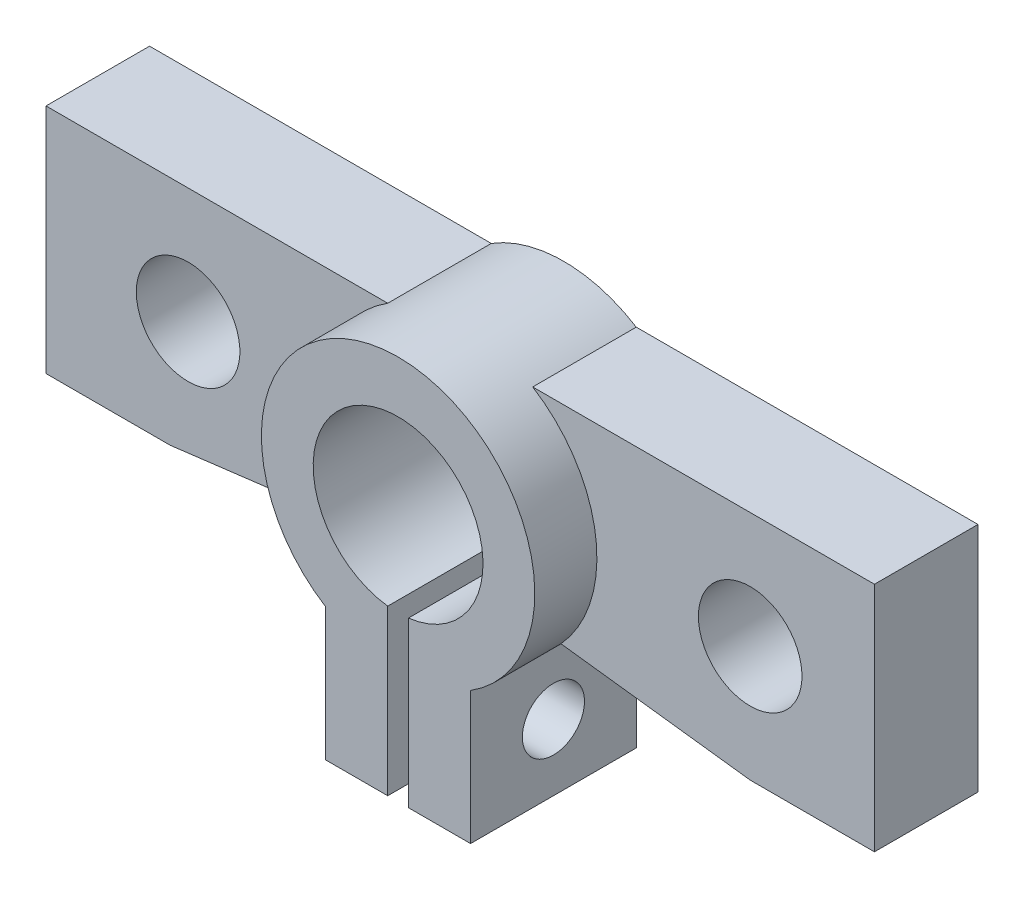
SolidWorks part; units mm, degrees
material "ABS"
ref_plane "Front Plane" through (0, 0, 0) normal (1, 0, 0) x (0, 1, 0)
ref_plane "Top Plane" through (0, 0, 0) normal (0, 0, 1) x (0, 1, 0)
ref_plane "Right Plane" through (0, 0, 0) normal (0, 1, 0) x (-1, 0, 0)
sketch "Sketch1" plane through (0, 0, 0) normal (0, 0, 1) x (0, 1, 0)
  line L0 (-12, 3.5) -> (-5.5955, 3.5)
  line L5 (-12, 3.5) -> (-12, 0.5)
  line L6 (-12, 0.5) -> (-4.0694, 0.5)
  line L7 (-12, -0.5) -> (-4.0694, -0.5)
  line L8 (-12, -0.5) -> (-12, -3.5)
  line L9 (-12, -3.5) -> (-5.5955, -3.5)
  line L10 (1000, 0) -> (4.1, 0) construction
  line L11 (-4.1, 0) -> (-6.6, 0) construction
  line L12 (-6.6, 0) -> (-1015.8416, 0) construction
  line L13 (4.1, 0) -> (-4.1, 0) construction
  arc A0 (-5.5955, -3.5) -> (-5.5955, 3.5) centre (0, 0) ccw
  arc A1 (-4.0694, -0.5) -> (-4.0694, 0.5) centre (0, 0) ccw
  arc A2 (-6.581, 0.5) -> (-6.6, 0) centre (0, 0) ccw construction
  arc A3 (-6.6, 0) -> (-6.581, -0.5) centre (0, 0) ccw construction
  arc A4 (-5.5955, 3.5) -> (-6.581, 0.5) centre (0, 0) ccw construction
  arc A5 (-6.581, -0.5) -> (-5.5955, -3.5) centre (0, 0) ccw construction
  arc A6 (-4.1, 0) -> (-4.0694, -0.5) centre (0, 0) ccw construction
  arc A7 (-4.0694, 0.5) -> (-4.1, 0) centre (0, 0) ccw construction
  point P752 (0, 0)
  dimension "D1" = 8.2
  dimension "D2" = 13.2
  dimension "D3" = 3
  dimension "D4" = 3
  dimension "D5" = 0.5
  dimension "D6" = 0.5
  dimension "D7" = 12
extrude "Boss-Extrude1" add sketch "Sketch1" along normal blind 8
sketch "Sketch2" plane through (-3.5, 0, 0) normal (-1, 0, 0) x (0, -1, 0)
  line L0 (8.7978, 8) -> (8.7978, 0) construction
  line L1 (5.5955, 8) -> (12, 8) construction
  line L2 (5.5955, 0) -> (12, 0) construction
  circle A0 centre (8.7978, 4) radius 1.5
  dimension "D1" = 3
extrude "Cut-Extrude1" cut sketch "Sketch2" against normal blind 8 contours L0 A0 | A0 L0
sketch "Sketch4" plane through (0, 0, 0) normal (0, 0, -1) x (1, 0, 0)
  line L0 (0.6849, 0) -> (10.7733, 0) construction
  line L1 (14, 5.5955) -> (20, 5.5955)
  line L2 (20, 5.5955) -> (20, -5.5955)
  line L3 (20, -5.5955) -> (3.5, -5.5955)
  line L4 (14, 5.5955) -> (4.863, 4.4622)
  line L5 (3.5, 5.5955) -> (14, 5.5955) construction
  line L6 (-3.5, -5.5955) -> (-20, -5.5955)
  line L7 (-20, -5.5955) -> (-20, 5.5955)
  line L8 (-20, 5.5955) -> (-14, 5.5955)
  line L9 (-4.863, 4.4622) -> (-14, 5.5955)
  line L10 (-14, 5.5955) -> (-3.5, 5.5955) construction
  arc A0 (-3.5, 5.5955) -> (3.5, 5.5955) centre (0, 0) ccw construction
  circle A1 centre (14, 0) radius 2.5
  circle A2 centre (-13.1394, 0) radius 2.5
  arc M7 (-3.5, 5.5955) -> (3.5, 5.5955) centre (0, 0) ccw
  dimension "D4" = 5
  dimension "D1" = 20
  dimension "D2" = 20
  dimension "D3" = 6
extrude "Boss-Extrude2" add sketch "Sketch4" against normal blind 5 contours L1 L4 L3 L2 A1 M7 | L9 L8 L7 L6 A2 M7
equation "\"D2@Sketch1\"=\"D1@Sketch1\"+5"
equation "\"extrusion_width\"= 20mm"
equation "\"frame_height\"= 360mm"
equation "\"frame_width\"= 320mm"
equation "\"frame_length\"= 320mm"
equation "\"bed_radius\"= 100mm"
equation "\"D4@Sketch1\"=\"D3@Sketch1\""
equation "\"D6@Sketch1\"=\"D5@Sketch1\""
equation "\"D2@Sketch4\"=\"D1@Sketch4\""
equation "\"hole_for_extrusion_mounting\"= 5mm"
equation "\"cantilever_support_thickness\"= 5mm"
equation "\"D4@Sketch4\"=\"hole_for_extrusion_mounting\""
